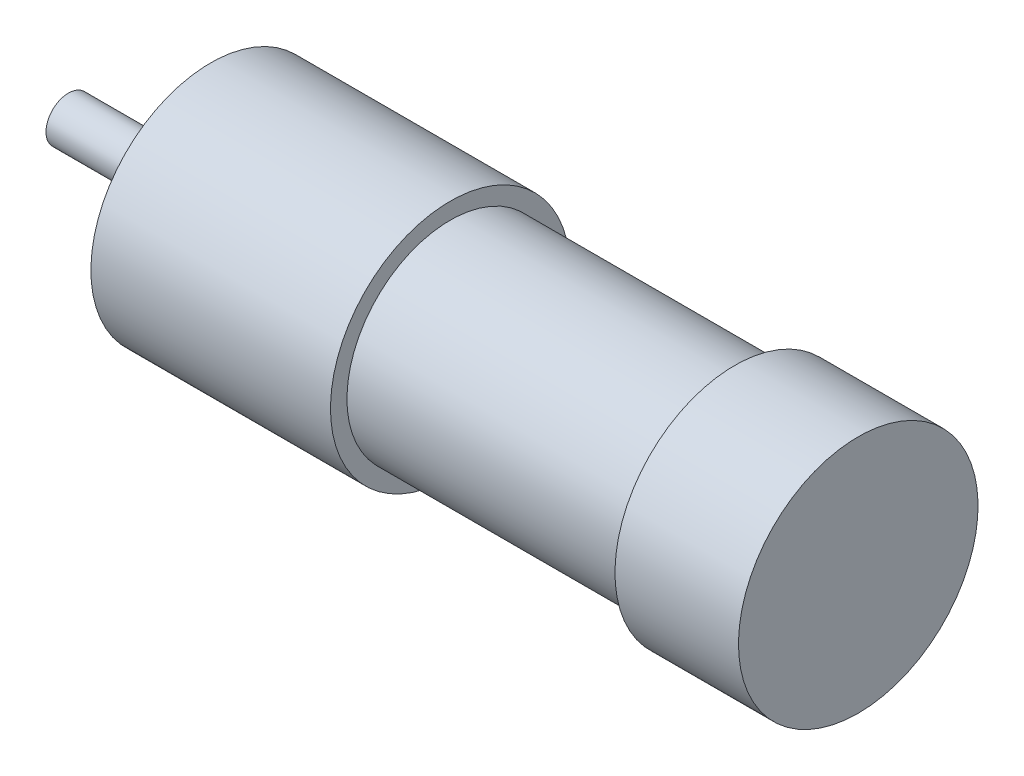
SolidWorks part; units mm, degrees
ref_plane "Front Plane" through (0, 0, 0) normal (0, 0, 1) x (1, 0, 0)
ref_plane "Top Plane" through (0, 0, 0) normal (0, 1, 0) x (1, 0, 0)
ref_plane "Right Plane" through (0, 0, 0) normal (1, 0, 0) x (0, 0, -1)
sketch "Sketch1" plane through (0, 0, 0) normal (0, 0, 1) x (1, 0, 0)
  line L0 (0, 0) -> (73, 0) construction
  line L1 (0, 0) -> (0, 10)
  line L2 (0, 10) -> (3, 10)
  line L3 (3, 10) -> (3, 16)
  line L4 (3, 16) -> (35, 16)
  line L5 (35, 16) -> (35, 13.8)
  line L6 (35, 13.8) -> (73, 13.8)
  line L7 (73, 13.8) -> (73, 0)
  line L8 (0, 0) -> (73, 0)
  dimension "D1" = 32
  dimension "D2" = 38
  dimension "D3" = 13.8
  dimension "D4" = 16
  dimension "D5" = 10
  dimension "D6" = 3
revolve "Revolve1" add sketch "Sketch1" angle 360 about L0
sketch "Sketch2" plane through (0, 0, 0) normal (0, 0, 1) x (1, 0, 0)
  line L1 (73, -13.8) -> (73, 13.8) construction
  line L2 (73, 16) -> (89.5, 16)
  line L8 (73, 0) -> (89.5, 0) construction
  line L9 (73, 16) -> (73, 0)
  line L10 (89.5, 0) -> (89.5, 16)
  line L11 (89.5, 0) -> (73, 0)
  dimension "D1" = 16.5
revolve "Revolve2" add sketch "Sketch2" angle 360 about L8
sketch "Sketch4" plane through (3, 0, 0) normal (-1, 0, 0) x (0, 0, 1)
  line L0 (0, 0) -> (9.1924, 9.1924) construction
  line L1 (0, 0) -> (13, 0) construction
  circle A0 centre (0, 0) radius 13 construction
  circle A1 centre (9.1924, 9.1924) radius 2
  circle A2 centre (9.1924, -9.1924) radius 2
  circle A3 centre (-9.1924, -9.1924) radius 2
  circle A4 centre (-9.1924, 9.1924) radius 2
  point P15 (0, 0)
  dimension "D1" = 26
  dimension "D3" = 4
  dimension "D2" = 45
  dimension "D4" = 4
extrude "Cut-Extrude1" cut sketch "Sketch4" against normal blind 8
sketch "Sketch5" plane through (0, 0, 0) normal (-1, 0, 0) x (0, 0, 1)
  line L0 (-3.937, 9.1924) -> (3.937, 9.1924)
  line L1 (-3.937, -9.1924) -> (3.937, -9.1924)
  circle A0 centre (9.1924, 9.1924) radius 2 construction
  circle A4 centre (0, 0) radius 10 construction
  circle A5 centre (0, 0) radius 10 construction
  arc A6 (-3.937, 9.1924) -> (-3.937, -9.1924) centre (0, 0) ccw
  circle A7 centre (9.1924, -9.1924) radius 2 construction
  arc A11 (3.937, -9.1924) -> (3.937, 9.1924) centre (0, 0) ccw
  circle A12 centre (0, 0) radius 3
  circle A13 centre (0, 0) radius 10
  dimension "D1" = 6
extrude "Boss-Extrude1" add sketch "Sketch5" along normal blind 16 contours A12
sketch "Sketch6" plane through (0, 0, 0) normal (-1, 0, 0) x (0, 0, 1)
  line L0 (-4.3589, 9) -> (4.3589, 9)
  line L1 (-4.3589, -9) -> (4.3589, -9)
  circle A1 centre (0, 0) radius 10
  circle A2 centre (0, 0) radius 10
  circle M3 centre (0, 0) radius 10
  dimension "D2" = 18
  dimension "D1" = 0
extrude "Cut-Extrude2" cut sketch "Sketch6" against normal blind 3 contours L1 M3 | L0 M3
